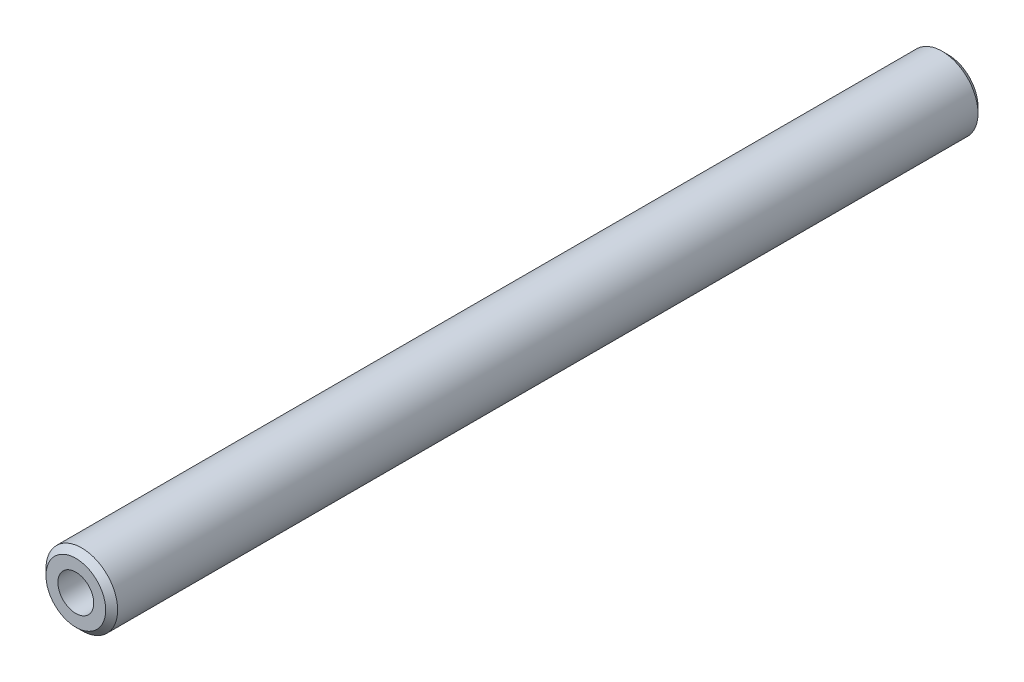
SolidWorks part; units mm, degrees
material "6061 合金"
ref_plane "前视基准面" through (0, 0, 0) normal (0, 0, 1) x (1, 0, 0)
ref_plane "上视基准面" through (0, 0, 0) normal (0, 1, 0) x (1, 0, 0)
ref_plane "右视基准面" through (0, 0, 0) normal (1, 0, 0) x (0, 0, -1)
other "Configuration Table"
sketch "草图1" plane through (0, 0, 0) normal (0, 0, 1) x (1, 0, 0)
  circle A0 centre (0, 0) radius 3
  circle A1 centre (0, 0) radius 6
  dimension "D1" = 6
  dimension "D2" = 12
extrude "凸台-拉伸1" add sketch "草图1" along normal blind 146
chamfer "倒角1" distance 1 angle 45 2 edges at (6, 0, 146) (6, 0, 0)
